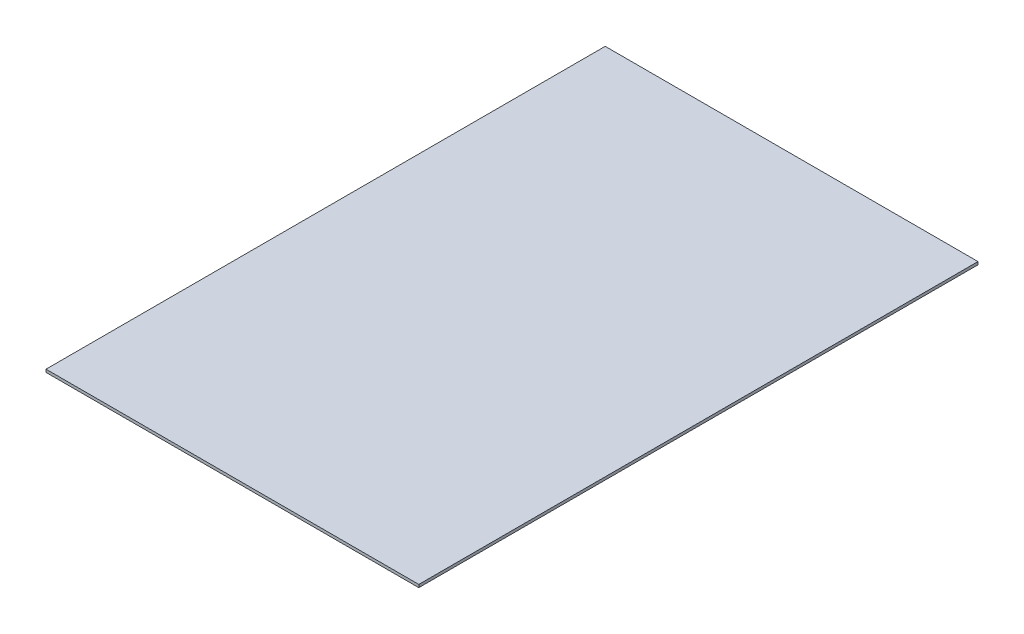
SolidWorks part; units mm, degrees
ref_plane "Front Plane" through (0, 0, 0) normal (0, 0, 1) x (1, 0, 0)
ref_plane "Top Plane" through (0, 0, 0) normal (0, 1, 0) x (1, 0, 0)
ref_plane "Right Plane" through (0, 0, 0) normal (1, 0, 0) x (0, 0, -1)
sketch "Sketch1" plane through (0, 0, 0) normal (0, 1, 0) x (1, 0, 0)
  line L1 (0, 0) -> (200, 0)
  line L2 (0, 0) -> (0, 300)
  line L3 (0, 300) -> (200, 300)
  line L4 (200, 0) -> (200, 300)
  line L5 (0, 0) -> (200, 300) construction
  line L6 (0, 300) -> (200, 0) construction
  point P4 (100, 150)
  dimension "D1" = 200
  dimension "D2" = 300
extrude "Boss-Extrude1" add sketch "Sketch1" along normal blind 1.52
